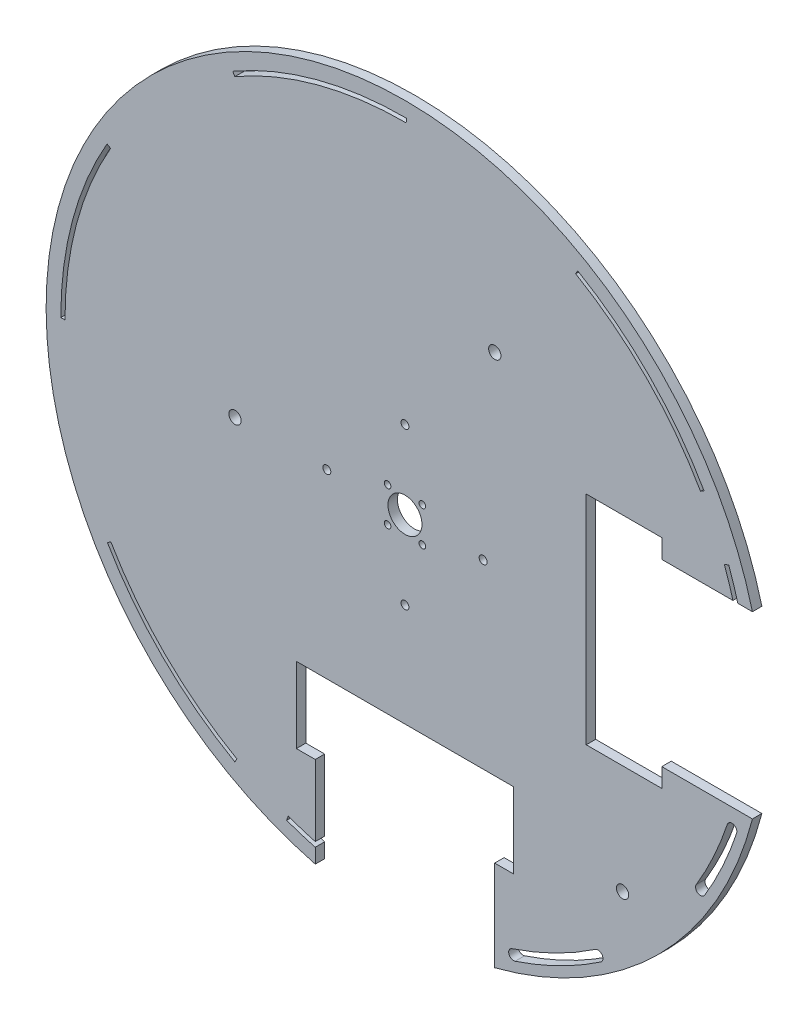
SolidWorks part; units mm, degrees
ref_plane "Front Plane" through (0, 0, 0) normal (0, 0, 1) x (1, 0, 0)
ref_plane "Top Plane" through (0, 0, 0) normal (0, 1, 0) x (1, 0, 0)
ref_plane "Right Plane" through (0, 0, 0) normal (1, 0, 0) x (0, 0, -1)
sketch "Sketch1" plane through (0, 0, 0) normal (0, 0, 1) x (1, 0, 0)
  line L0 (0, 190) -> (0, -190) construction
  line L1 (47.5, -183.9667) -> (47.5, -135.9667)
  line L2 (47.5, -135.9667) -> (57.5, -135.9667)
  line L3 (57.5, -135.9667) -> (57.5, -95.9667)
  line L4 (57.5, -95.9667) -> (-57.5, -95.9667)
  line L5 (-47.5, -183.9667) -> (-47.5, -135.9667)
  line L6 (-47.5, -135.9667) -> (-57.5, -135.9667)
  line L7 (-57.5, -135.9667) -> (-57.5, -95.9667)
  line L8 (-95.9667, -57.5) -> (-95.9667, 57.5) [skipped]
  line L9 (-135.9667, -57.5) -> (-95.9667, -57.5) [skipped]
  line L10 (-135.9667, -47.5) -> (-135.9667, -57.5) [skipped]
  line L11 (-183.9667, -47.5) -> (-135.9667, -47.5) [skipped]
  line L12 (-183.9667, 47.5) -> (-135.9667, 47.5) [skipped]
  line L13 (-135.9667, 47.5) -> (-135.9667, 57.5) [skipped]
  line L14 (-135.9667, 57.5) -> (-95.9667, 57.5) [skipped]
  line L15 (-57.5, 95.9667) -> (57.5, 95.9667) [skipped]
  line L16 (-57.5, 135.9667) -> (-57.5, 95.9667) [skipped]
  line L17 (-47.5, 135.9667) -> (-57.5, 135.9667) [skipped]
  line L18 (-47.5, 183.9667) -> (-47.5, 135.9667) [skipped]
  line L19 (47.5, 183.9667) -> (47.5, 135.9667) [skipped]
  line L20 (47.5, 135.9667) -> (57.5, 135.9667) [skipped]
  line L21 (57.5, 135.9667) -> (57.5, 95.9667) [skipped]
  line L22 (95.9667, 57.5) -> (95.9667, -57.5)
  line L23 (135.9667, 57.5) -> (95.9667, 57.5)
  line L24 (135.9667, 47.5) -> (135.9667, 57.5)
  line L25 (183.9667, 47.5) -> (135.9667, 47.5)
  line L26 (183.9667, -47.5) -> (135.9667, -47.5)
  line L27 (135.9667, -47.5) -> (135.9667, -57.5)
  line L28 (135.9667, -57.5) -> (95.9667, -57.5)
  line L29 (0, 0) -> (-65.2193, -178.4557) construction
  line L30 (-61.7867, -169.0633) -> (-62.6449, -171.4114)
  line L31 (0, 0) -> (178.4557, 65.2193) construction
  line L32 (169.0633, 61.7867) -> (171.4114, 62.6449)
  line L33 (0, 0) -> (165.1633, 93.9207) construction
  line L34 (0, 0) -> (-95.0715, 164.5035) construction
  line L35 (0, 0) -> (95.3894, 164.3194) construction
  line L36 (0, 0) -> (-164.5035, 95.0715) construction
  line L37 (0, 0) -> (-189.9987, -0.7115) construction
  line L38 (0, 0) -> (-164.3194, -95.3894) construction
  line L39 (-93.9207, -165.1633) -> (0, 0) construction
  line L40 (158.3829, 90.065) -> (156.4705, 88.9775)
  line L41 (91.4734, 157.5737) -> (90.3689, 155.671)
  line L42 (0, 0) -> (0.7115, 189.9987) construction
  line L43 (0.6823, 182.1987) -> (0.674, 179.9987)
  line L44 (-91.1685, 157.7502) -> (-90.0677, 155.8455)
  line L45 (-182.1987, -0.6823) -> (-179.9987, -0.674)
  line L46 (-157.7502, 91.1685) -> (-155.8455, 90.0677)
  line L47 (-90.065, -158.3829) -> (-88.9775, -156.4705)
  line L48 (-157.5737, -91.4734) -> (-155.671, -90.3689)
  line L49 (-134.3503, 134.3503) -> (134.3503, -134.3503) construction
  line L50 (-134.3503, -134.3503) -> (134.3503, 134.3503) construction
  line L51 (-95.9667, 0) -> (95.9667, 0) construction
  arc A0 (47.5, -183.9667) -> (183.9667, -47.5) centre (0, 0) ccw
  arc A1 (183.9667, 47.5) -> (-47.5, -183.9667) centre (0, 0) ccw
  arc A2 (-47.5, -173.6196) -> (-61.7867, -169.0633) centre (0, 0) cw
  arc A3 (-47.5, -176.2101) -> (-62.6449, -171.4114) centre (0, 0) cw
  arc A4 (-61.7867, -169.0633) -> (-88.9775, -156.4705) centre (0, 0) cw construction
  arc A5 (173.6196, 47.5) -> (169.0633, 61.7867) centre (0, 0) ccw
  arc A6 (176.2101, 47.5) -> (171.4114, 62.6449) centre (0, 0) ccw
  arc A7 (169.0633, 61.7867) -> (156.4705, 88.9775) centre (0, 0) ccw construction
  arc A8 (-88.9775, -156.4705) -> (-155.671, -90.3689) centre (0, 0) cw
  arc A9 (-155.671, -90.3689) -> (-179.9987, -0.674) centre (0, 0) cw construction
  arc A10 (156.4705, 88.9775) -> (90.3689, 155.671) centre (0, 0) ccw
  arc A11 (90.3689, 155.671) -> (0.674, 179.9987) centre (0, 0) ccw construction
  arc A12 (0.674, 179.9987) -> (-90.0677, 155.8455) centre (0, 0) ccw
  arc A13 (-179.9987, -0.674) -> (-155.8455, 90.0677) centre (0, 0) cw
  arc A14 (-90.0677, 155.8455) -> (-155.8455, 90.0677) centre (0, 0) ccw construction
  arc A15 (158.3829, 90.065) -> (91.4734, 157.5737) centre (0, 0) ccw
  arc A16 (-91.1685, 157.7502) -> (0.6823, 182.1987) centre (0, 0) cw
  arc A17 (-182.1987, -0.6823) -> (-157.7502, 91.1685) centre (0, 0) cw
  arc A18 (-157.5737, -91.4734) -> (-90.065, -158.3829) centre (0, 0) ccw
  circle A19 centre (0, 0) radius 9
  circle A21 centre (-9.1924, 9.1924) radius 1.75
  circle A33 centre (0, 0) radius 102.5 construction
  circle A34 centre (115.2062, -115.2062) radius 3.25
  circle A37 centre (-89.9994, -0.337) radius 3.25
  circle A38 centre (47.5531, 98.2245) radius 3.25
  circle A39 centre (0, 0) radius 122.5 construction
  circle A40 centre (9.1924, 9.1924) radius 1.75
  circle A41 centre (9.1924, -9.1924) radius 1.75
  circle A42 centre (-9.1924, -9.1924) radius 1.75
  circle A43 centre (41.37, 0) radius 2.1
  circle A44 centre (0, -41.37) radius 2.1
  circle A45 centre (-41.37, 0) radius 2.1
  circle A46 centre (0, 41.37) radius 2.1
  arc A53 (173.0997, -57.5) -> (156.4452, -93.7798) centre (0, 0) cw construction
  arc A54 (158.6752, -95.1166) -> (175.5671, -58.3196) centre (0, 0) ccw
  arc A55 (154.2152, -92.4431) -> (170.6323, -56.6804) centre (0, 0) ccw
  arc A56 (154.2152, -92.4431) -> (158.6752, -95.1166) centre (156.4452, -93.7798) ccw
  arc A57 (175.5671, -58.3196) -> (170.6323, -56.6804) centre (173.0997, -57.5) ccw
  arc A58 (57.5, -173.0997) -> (102.2117, -151.0713) centre (0, 0) ccw construction
  arc A59 (58.3196, -175.5671) -> (103.6686, -153.2247) centre (0, 0) ccw
  arc A60 (56.6804, -170.6323) -> (100.7547, -148.9179) centre (0, 0) ccw
  arc A61 (56.6804, -170.6323) -> (58.3196, -175.5671) centre (57.5, -173.0997) ccw
  arc A62 (103.6686, -153.2247) -> (100.7547, -148.9179) centre (102.2117, -151.0713) ccw
  point P14 (0, -95.9667)
  point P40 (0, 0)
  point P76 (0, 0)
  point P81 (0, 0)
  point P90 (0, 0)
  point P91 (165.768, -76.0969)
  point P101 (0, 0)
  point P112 (0, 0)
  point P113 (0, 0)
  point P116 (80.6118, -163.62)
  dimension "D1" = 380
  dimension "D7" = 15
  dimension "D8" = 30
  dimension "D9" = 15
  dimension "D10" = 30
  dimension "D12" = 94
  dimension "D15" = 95
  dimension "D17" = 94.0914
  dimension "D18" = 180
  dimension "D20" = 182.5
  dimension "D21" = 4
  dimension "D19" = 45
  dimension "D24" = 3.5
  dimension "D26" = 41.37
  dimension "D27" = 4
  dimension "D30" = 10
  dimension "D32" = 40
  dimension "D33" = 10
  dimension "D35" = 18
  dimension "D36" = 205
  dimension "D37" = 6.5
  dimension "D38" = 6.5
  dimension "D39" = 90
  dimension "D40" = 6.5
  dimension "D42" = 50
  dimension "D22" = 4.2
  dimension "D28" = 5
  dimension "D29" = 5
  dimension "D31" = 5.2
  dimension "D34" = 5.2
  dimension "D2" = 47.5
  dimension "D3" = 48
  dimension "D4" = 10
  dimension "D5" = 40
  dimension "D11" = 95
  dimension "D13" = 95
  dimension "D14" = 94
  dimension "D16" = 95
  dimension "D23" = 90
  dimension "D25" = 13
  dimension "D41" = 109.13
  dimension "D6" = 4
extrude "Boss-Extrude1" add sketch "Sketch1" along normal blind 5
